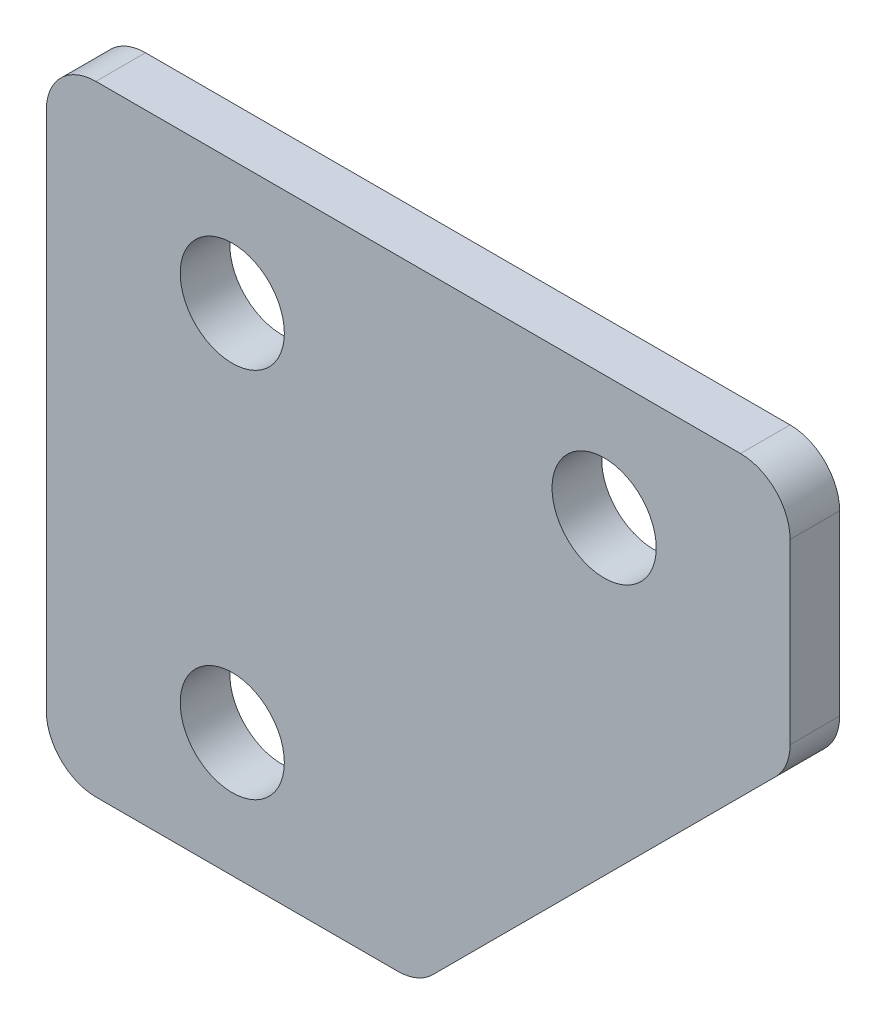
SolidWorks part; units mm, degrees
material "5052-H34"
ref_plane "正面" through (0, 0, 0) normal (0, 0, 1) x (1, 0, 0)
ref_plane "平面" through (0, 0, 0) normal (0, 1, 0) x (1, 0, 0)
ref_plane "右側面" through (0, 0, 0) normal (1, 0, 0) x (0, 0, -1)
sketch "ｽｹｯﾁ1" plane through (0, 0, 0) normal (0, 0, 1) x (1, 0, 0)
  line L0 (0, 0) -> (0, -15) construction
  line L1 (0, 0) -> (15, 0) construction
  line L2 (22.5, -5) -> (7.5, -20)
  line L3 (-7.5, 5) -> (7.5, 5)
  line L4 (-7.5, 5) -> (-7.5, -20)
  line L5 (-7.5, -20) -> (7.5, -20)
  line L6 (7.5, 5) -> (7.5, -20)
  line L7 (-7.5, 5) -> (7.5, -20) construction
  line L8 (-7.5, -20) -> (7.5, 5) construction
  line L9 (7.5, 5) -> (22.5, 5)
  line L10 (7.5, 5) -> (7.5, -5)
  line L11 (7.5, -5) -> (22.5, -5)
  line L12 (22.5, 5) -> (22.5, -5)
  circle A0 centre (0, 0) radius 2.1
  circle A1 centre (0, -15) radius 2.1
  circle A2 centre (15, 0) radius 2.1
  point P7 (0, -7.5)
  dimension "D1" = 4.2
  dimension "D2" = 4.2
  dimension "D3" = 15
  dimension "D4" = 15
  dimension "D5" = 15
  dimension "D6" = 25
  dimension "D7" = 10
  dimension "D8" = 15
extrude "ﾎﾞｽ - 押し出し1" add sketch "ｽｹｯﾁ1" along normal blind 2 contours L6 L3 L4 L5 A1 A0 | L11 L6 L2 | L12 L9 L6 L11 A2
fillet "ﾌｨﾚｯﾄ1" radius 2 5 edges at (22.5, 5, 1) (22.5, -5, 1) (7.5, -20, 1) (-7.5, -20, 1) (-7.5, 5, 1)
